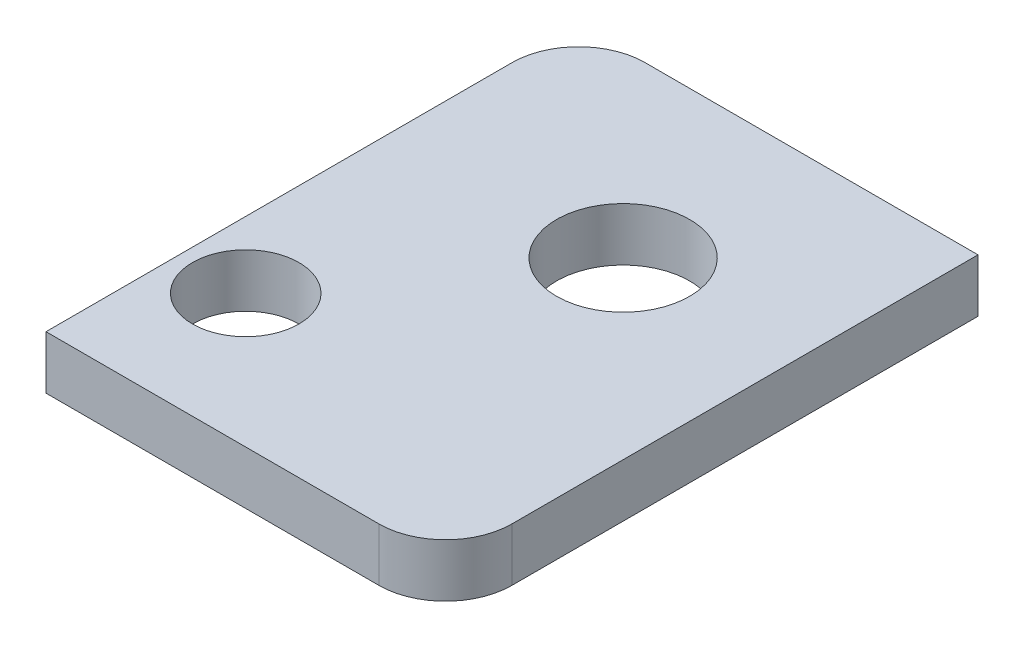
SolidWorks part; units mm, degrees
ref_plane "Front Plane" through (0, 0, 0) normal (0, 0, 1) x (1, 0, 0)
ref_plane "Top Plane" through (0, 0, 0) normal (0, 1, 0) x (1, 0, 0)
ref_plane "Right Plane" through (0, 0, 0) normal (1, 0, 0) x (0, 0, -1)
sketch "Sketch1" plane through (0, 0, 0) normal (0, 1, 0) x (1, 0, 0)
  line L0 (0, 0) -> (0, 35)
  line L3 (25, 0) -> (0, 0)
  line L4 (5, 40) -> (30, 40)
  line L5 (30, 40) -> (30, 5)
  circle A2 centre (5, 10) radius 4
  arc A8 (25, 0) -> (30, 5) centre (25, 5) ccw
  arc A9 (0, 35) -> (5, 40) centre (5, 35) cw
  circle A10 centre (16.8726, 26.4739) radius 5
  point P8 (0, 40)
  dimension "D1" = 30
  dimension "D2" = 8
  dimension "D9" = 5
  dimension "D3" = 5
  dimension "D4" = 10
  dimension "D8" = 40
extrude "Boss-Extrude1" add sketch "Sketch1" along normal blind 4
